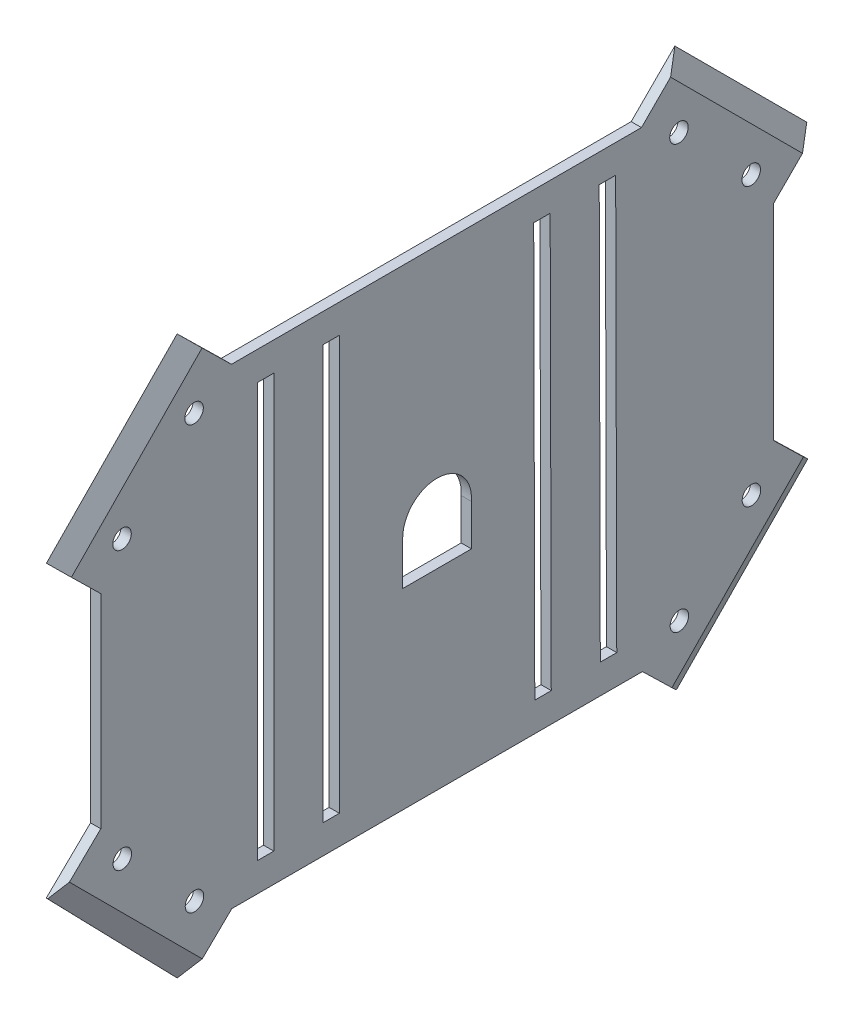
SolidWorks part; units mm, degrees
ref_plane "Alzado" through (0, 0, 0) normal (0, 0, 1) x (1, 0, 0)
ref_plane "Planta" through (0, 0, 0) normal (0, 1, 0) x (1, 0, 0)
ref_plane "Vista lateral" through (0, 0, 0) normal (1, 0, 0) x (0, 0, -1)
sketch "Croquis1" plane through (0, 0, 0) normal (1, 0, 0) x (0, 0, -1)
  line L0 (-49.88, -57.285) -> (49.88, -57.285)
  line L1 (-81.7, -24.565) -> (-81.7, 24.905)
  line L2 (81.7, -24.565) -> (81.7, 25.235)
  line L3 (-49.95, 57.285) -> (49.65, 57.285)
  line L4 (-81.7, -57.285) -> (81.7, 57.285) construction
  line L5 (81.7, -57.285) -> (-81.7, 57.285) construction
  line L6 (-49.95, 57.285) -> (-81.7, 24.905)
  line L7 (49.65, 57.285) -> (81.7, 25.235)
  line L8 (81.7, -24.565) -> (49.88, -57.285)
  line L9 (-81.7, -24.565) -> (-49.88, -57.285)
  point P1 (0, 0)
  dimension "D1" = 163.4
  dimension "D2" = 114.57
  dimension "D3" = 32.38
  dimension "D4" = 31.75
  dimension "D5" = 32.05
  dimension "D6" = 32.05
  dimension "D7" = 31.82
  dimension "D8" = 32.72
  dimension "D9" = 31.82
  dimension "D10" = 32.72
extrude "Saliente-Extruir1" add sketch "Croquis1" along normal blind 2.5
sketch "Croquis2" plane through (2.5, 0, 0) normal (1, 0, 0) x (0, 0, -1)
  line L0 (81.7, 25.235) -> (49.65, 57.285)
  line L1 (81.7, 25.235) -> (92.3066, 35.8416)
  line L2 (49.65, 57.285) -> (60.2566, 67.8916)
  line L3 (92.3066, 35.8416) -> (60.2566, 67.8916)
  line L4 (-81.7, 24.905) -> (-49.95, 57.285)
  line L5 (-81.7, 24.905) -> (-92.4103, 35.4069)
  line L6 (-49.95, 57.285) -> (-60.6603, 67.7869)
  line L7 (-92.4103, 35.4069) -> (-60.6603, 67.7869)
  line L8 (-81.7, -24.565) -> (-49.88, -57.285)
  line L9 (-81.7, -24.565) -> (-92.4535, -35.0227)
  line L10 (-49.88, -57.285) -> (-60.6335, -67.7427)
  line L11 (-92.4535, -35.0227) -> (-60.6335, -67.7427)
  line L12 (49.88, -57.285) -> (81.7, -24.565)
  line L13 (49.88, -57.285) -> (60.6335, -67.7427)
  line L14 (81.7, -24.565) -> (92.4535, -35.0227)
  line L15 (60.6335, -67.7427) -> (92.4535, -35.0227)
  dimension "D1" = 15
  dimension "D2" = 15
  dimension "D3" = 15
  dimension "D4" = 15
extrude "Saliente-Extruir2" add sketch "Croquis2" against normal blind 2.5
sketch "Croquis3" plane through (2.5, 0, 0) normal (1, 0, 0) x (0, 0, -1)
  line L4 (-92.4103, 35.4069) -> (-60.6603, 67.7869) construction
  line L5 (-92.4103, 35.4069) -> (-81.7, 24.905) construction
  line L6 (-60.6603, 67.7869) -> (-49.95, 57.285) construction
  line L7 (-81.7, 24.905) -> (-49.95, 57.285) construction
  line L8 (-81.7, 0.17) -> (81.7, 0.335) construction
  line L9 (-81.7, 24.905) -> (-81.7, -24.565) construction
  line L10 (81.7, -24.565) -> (81.7, 25.235) construction
  line L11 (-0.15, 57.285) -> (0, -57.285) construction
  line L12 (49.65, 57.285) -> (-49.95, 57.285) construction
  line L13 (-49.88, -57.285) -> (49.88, -57.285) construction
  line L14 (-8.35, 0) -> (-8.35, -10.6984)
  line L15 (-8.35, -10.6984) -> (8.3471, -10.6984)
  line L16 (8.3471, -10.6984) -> (8.3217, -0.6867)
  line L17 (23.4695, 50.3468) -> (23.7328, -50.2228)
  line L18 (-49.95, 57.285) -> (49.65, 57.285) construction
  line L19 (-49.95, 57.285) -> (-49.95, 50.285) construction
  line L20 (-49.95, 50.285) -> (49.65, 50.285) construction
  line L21 (49.65, 57.285) -> (49.65, 50.285) construction
  line L22 (-43.6645, 50.285) -> (-39.6645, 50.285)
  line L23 (-43.6645, 50.285) -> (-43.6645, -50.285)
  line L24 (-43.6645, -50.285) -> (-39.6645, -50.285)
  line L25 (-39.6645, 50.285) -> (-39.6645, -50.285)
  line L26 (-27.7512, 50.285) -> (-23.7512, 50.285)
  line L27 (-27.7512, 50.285) -> (-27.7512, -50.285)
  line L28 (-27.7512, -50.285) -> (-23.7512, -50.285)
  line L29 (-23.7512, 50.285) -> (-23.7512, -50.285)
  line L30 (27.7328, -50.2124) -> (23.7328, -50.2228)
  line L31 (27.4695, 50.3573) -> (27.7328, -50.2124)
  line L32 (27.4695, 50.3573) -> (23.4695, 50.3468)
  line L33 (39.3827, 50.3885) -> (39.646, -50.1812)
  line L34 (43.646, -50.1707) -> (39.646, -50.1812)
  line L35 (43.3827, 50.399) -> (43.646, -50.1707)
  line L36 (43.3827, 50.399) -> (39.3827, 50.3885)
  circle A0 centre (-76.5404, 33.851) radius 2.25
  circle A1 centre (-59.0422, 51.5508) radius 2.25
  circle A2 centre (76.3015, 34.0511) radius 2.25
  circle A3 centre (58.757, 51.7051) radius 2.25
  circle A4 centre (76.3696, -33.3919) radius 2.25
  circle A5 centre (58.8608, -51.0813) radius 2.25
  circle A6 centre (-58.9385, -51.165) radius 2.25
  circle A7 centre (-76.4724, -33.5005) radius 2.25
  arc A9 (8.3217, -0.6867) -> (-8.35, 0) centre (0, 0) ccw
  dimension "D4" = 10.46
  dimension "D5" = 16.7
  dimension "D6" = 7
  dimension "D7" = 7
  dimension "D1" = 4.5
  dimension "D2" = 4.5
  dimension "D3" = 10
  dimension "D8" = 4
  dimension "D9" = 4
  dimension "D10" = 7
extrude "Cortar-Extruir1" cut sketch "Croquis3" against normal blind 10
sketch "Croquis4" plane through (0, -28.145, 27.5974) normal (0, -0.714, 0.7001) x (1, 0, 0)
  line L6 (0, 90.772) -> (2.5, 90.772)
  line L7 (2.5, 90.772) -> (2.5, 85.772)
  line L8 (2.5, 90.772) -> (2.5, 75.772) construction
  line L9 (2.5, 85.772) -> (0, 90.772)
  line L13 (0, -90.7219) -> (2.5, -90.7219) construction
  line L14 (2.5, -75.722) -> (2.5, -90.7219) construction
  line L15 (2.5, -90.7219) -> (0, -90.7219)
  line L16 (2.5, -90.7219) -> (2.5, -85.7219)
  line L17 (2.5, -85.7219) -> (0, -90.7219)
  dimension "D1" = 5
  dimension "D2" = 5
extrude "Cortar-Extruir3" cut sketch "Croquis4" against normal blind 82
sketch "Croquis6" plane through (0, -28.2325, -28.2325) normal (0, -0.7071, -0.7071) x (1, 0, 0)
  line L0 (0, -90.6145) -> (2.5, -85.6145)
  line L1 (2.5, -75.6145) -> (2.5, -90.6145) construction
  line L2 (2.5, -85.6145) -> (2.5, -90.6145)
  line L3 (0, -90.6145) -> (2.5, -90.6145) construction
  line L4 (2.5, -90.6145) -> (0, -90.6145)
  line L5 (0, 90.7756) -> (2.5, 90.7756)
  line L6 (2.5, 90.7756) -> (2.5, 85.7756)
  line L7 (2.5, 90.7756) -> (2.5, 75.7771) construction
  line L8 (2.5, 85.7756) -> (0, 90.7756)
  dimension "D1" = 5
  dimension "D2" = 5
extrude "Cortar-Extruir4" cut sketch "Croquis6" against normal blind 90
